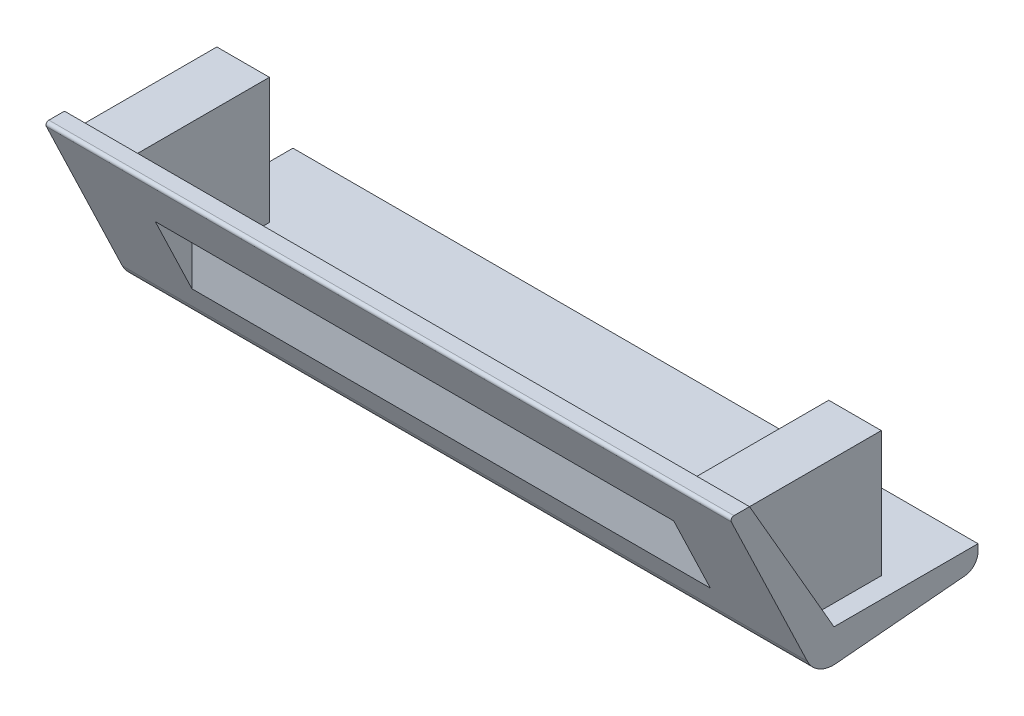
SolidWorks part; units mm, degrees
ref_plane "Front Plane" through (0, 0, 0) normal (0, 0, 1) x (1, 0, 0)
ref_plane "Top Plane" through (0, 0, 0) normal (0, 1, 0) x (1, 0, 0)
ref_plane "Right Plane" through (0, 0, 0) normal (1, 0, 0) x (0, 0, -1)
sketch "Sketch1" plane through (0, 0, 0) normal (1, 0, 0) x (0, 0, -1)
  line L0 (0, 0) -> (-29.3294, 50.8)
  line L1 (0, 0) -> (50, 0)
  line L2 (-29.3294, 50.8) -> (-36.3294, 50.8)
  line L3 (-36.3294, 50.8) -> (-6.2529, -12)
  line L4 (-6.2529, -12) -> (50, -7)
  line L5 (50, -7) -> (50, 0)
  line L6 (-6.2529, -12) -> (-6.2529, 0) construction
  line L7 (-12, 0) -> (0, 0) construction
  dimension "D1" = 50
  dimension "D2" = 60
  dimension "D3" = 50.8
  dimension "D4" = 7
  dimension "D5" = 7
  dimension "D6" = 12
extrude "Boss-Extrude2" add sketch "Sketch1" along normal mid plane 237.85
sketch "Sketch2" plane through (0, 0, 0) normal (0, 0, 1) x (1, 0, 0)
  line L0 (0, 0) -> (0, 50.8) construction
  line L5 (115.75, 47.625) -> (96.7, 47.625) construction
  line L6 (115.75, 47.625) -> (115.75, 3.175) construction
  line L11 (115.75, 3.175) -> (96.7, 3.175) construction
  line L12 (96.7, 47.625) -> (96.7, 3.175) construction
  line L14 (115.35, 47.225) -> (115.35, 3.575)
  line L15 (115.35, 3.575) -> (97.1, 3.575)
  line L28 (97.1, 47.225) -> (97.1, 3.575)
  line L29 (115.35, 47.225) -> (97.1, 47.225)
  line L30 (-96.7, 47.625) -> (-96.7, 3.175) construction
  line L31 (-115.75, 3.175) -> (-96.7, 3.175) construction
  line L32 (-115.75, 47.625) -> (-115.75, 3.175) construction
  line L33 (-115.75, 47.625) -> (-96.7, 47.625) construction
  line L34 (-115.35, 47.225) -> (-97.1, 47.225)
  line L35 (-97.1, 47.225) -> (-97.1, 3.575)
  line L36 (-115.35, 3.575) -> (-97.1, 3.575)
  line L37 (-115.35, 47.225) -> (-115.35, 3.575)
  line L39 (118.925, 0) -> (-118.925, 0) construction
  line L40 (118.925, 50.8) -> (-118.925, 50.8) construction
  line L41 (118.925, 0) -> (118.925, 50.8) construction
  dimension "D2" = 19.05
  dimension "D3" = 44.45
  dimension "D6" = 3.175
  dimension "D4" = 3.175
  dimension "D7" = 3.175
  dimension "D1" = 193.4
  dimension "D5" = 0.4
extrude "Boss-Extrude1" add sketch "Sketch2" along normal up to surface and the other way blind 20 up to face at (0, 25.4, 14.6647)
sketch "Sketch4" plane through (0, 0, 0) normal (1, 0, 0) x (0, 0, -1)
  line L1 (-26.7297, 30.7556) -> (-20, 34.641)
  line L2 (-36.3294, 50.8) -> (-6.2529, -12) construction
  line L3 (0, 0) -> (-29.3294, 50.8) construction
  line L4 (-20, 34.641) -> (-14, 24.2487)
  line L5 (-14, 24.2487) -> (-14, 4.176)
  line L8 (-26.7297, 30.7556) -> (-14, 4.176)
  point P1 (-25.2786, 27.7259)
  dimension "D1" = 12
  dimension "D2" = 14
extrude "Cut-Extrude2" cut sketch "Sketch4" against normal mid plane 180
fillet "Fillet1" radius 10 1 edges at (0, -12, 6.2529)
fillet "Fillet2" radius 5 1 edges at (0, -7, -50)
fillet "Fillet3" radius 1 1 edges at (0, 50.8, 36.3294)
equation "\"D1@Sketch2\"=187.05mm+0.25in"
